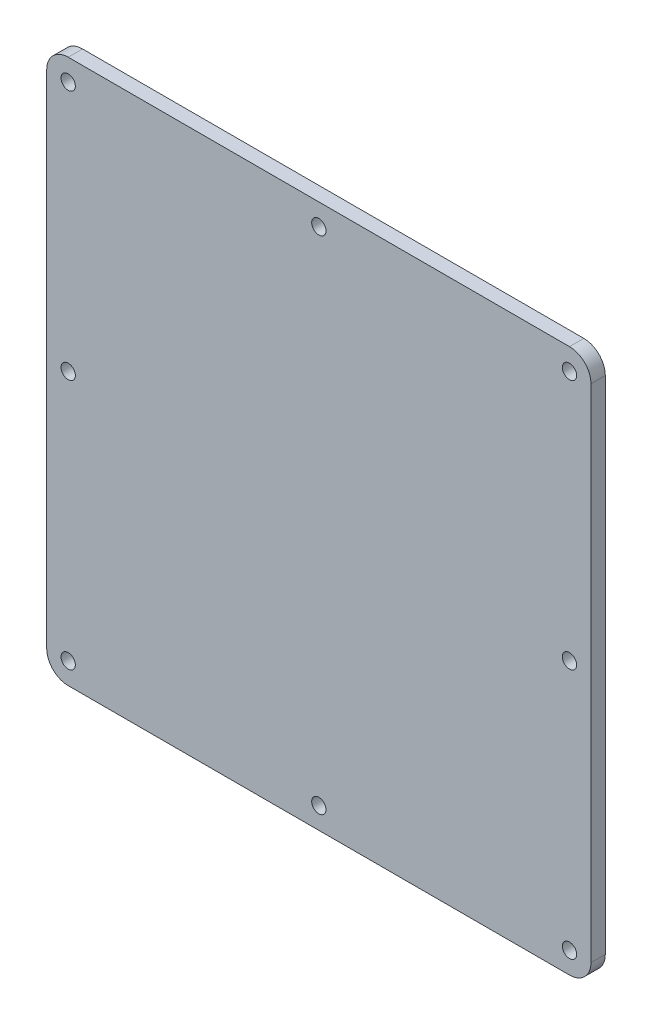
SolidWorks part; units mm, degrees
ref_plane "Front Plane" through (0, 0, 0) normal (0, 0, 1) x (1, 0, 0)
ref_plane "Top Plane" through (0, 0, 0) normal (0, 1, 0) x (1, 0, 0)
ref_plane "Right Plane" through (0, 0, 0) normal (1, 0, 0) x (0, 0, -1)
sketch "Sketch2" plane through (0, 0, 0) normal (0, 0, 1) x (1, 0, 0)
  line L0 (-175, 175) -> (175, 175) construction
  line L1 (-175, 190) -> (175, 190)
  line L2 (-190, 175) -> (-190, -175)
  line L3 (-175, -190) -> (175, -190)
  line L4 (190, 175) -> (190, -175)
  line L5 (-190, 190) -> (190, -190) construction
  line L6 (-190, -190) -> (190, 190) construction
  line L7 (175, 175) -> (175, -175) construction
  line L8 (175, -175) -> (-175, -175) construction
  line L9 (-175, -175) -> (-175, 175) construction
  arc A0 (-190, -175) -> (-175, -190) centre (-175, -175) ccw
  arc A1 (175, -190) -> (190, -175) centre (175, -175) ccw
  arc A2 (175, 190) -> (190, 175) centre (175, 175) cw
  arc A3 (-175, 190) -> (-190, 175) centre (-175, 175) ccw
  circle A4 centre (-175, 175) radius 5
  circle A5 centre (0, 175) radius 5
  circle A6 centre (175, 175) radius 5
  circle A14 centre (175, 0) radius 5
  circle A15 centre (-175, 0) radius 5
  circle A16 centre (-175, -175) radius 5
  circle A17 centre (0, -175) radius 5
  circle A18 centre (175, -175) radius 5
  point P0 (0, 0)
  dimension "D3" = 15
  dimension "D4" = 10
  dimension "D5" = 10
  dimension "D6" = 10
  dimension "D8" = 10
  dimension "D9" = 10
  dimension "D10" = 10
  dimension "D11" = 10
  dimension "D1" = 380
  dimension "D2" = 380
extrude "Boss-Extrude1" add sketch "Sketch2" along normal blind 10
